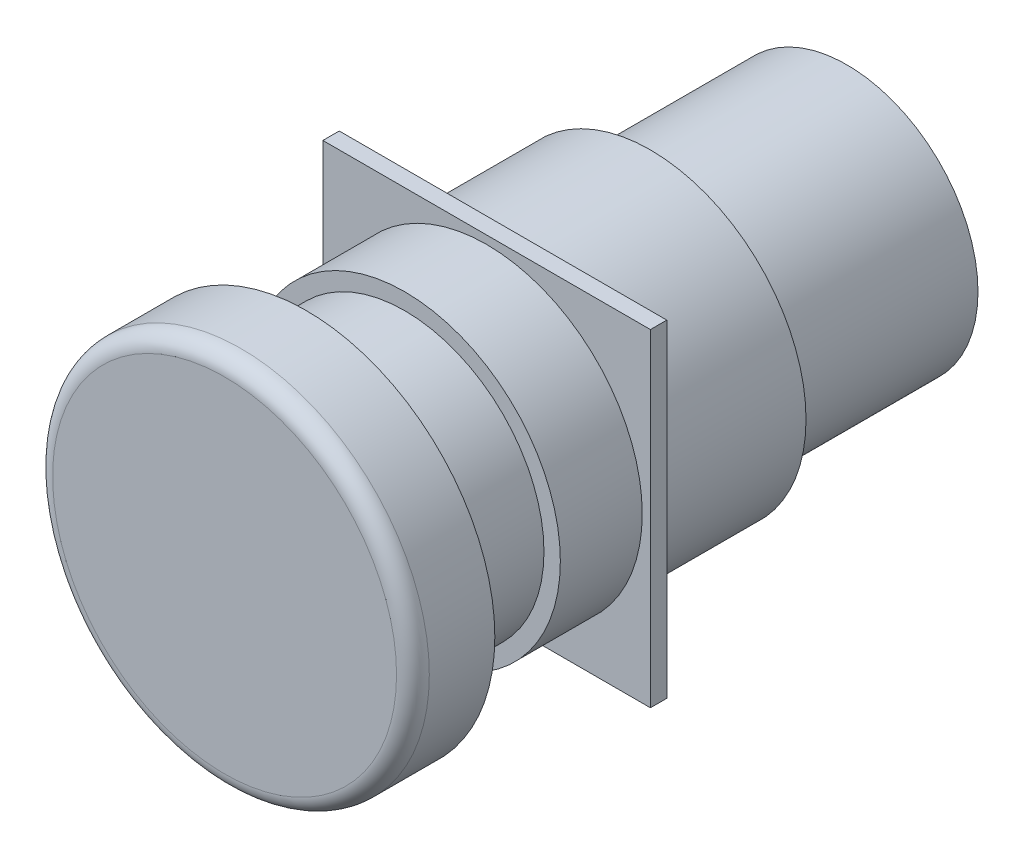
SolidWorks part; units mm, degrees
ref_plane "前视基准面" through (0, 0, 0) normal (0, 0, 1) x (1, 0, 0)
ref_plane "上视基准面" through (0, 0, 0) normal (0, 1, 0) x (1, 0, 0)
ref_plane "右视基准面" through (0, 0, 0) normal (1, 0, 0) x (0, 0, -1)
other "Configuration Table"
sketch "草图1" plane through (0, 0, 0) normal (0, 1, 0) x (1, 0, 0)
  line L0 (11.5, 0) -> (0, 0)
  line L1 (0, 0) -> (0, -5)
  line L2 (0, -5) -> (11.5, -5)
  line L3 (11.5, -5) -> (11.5, 0)
  line L4 (0, 0) -> (0, -5) construction
  dimension "D1" = 11.5
  dimension "D2" = 5
revolve "旋转1" add sketch "草图1" angle 360 about L4
sketch "草图2" plane through (0, 0, 0) normal (0, 0, -1) x (-1, 0, 0)
  circle A0 centre (0, 0) radius 10.5
  dimension "D1" = 21
extrude "切除-拉伸1" cut sketch "草图2" against normal blind 4
sketch "草图3" plane through (0, 0, 4) normal (0, 0, -1) x (-1, 0, 0)
  circle A0 centre (0, 0) radius 8.5
  dimension "D1" = 17
extrude "凸台-拉伸1" add sketch "草图3" along normal blind 10
ref_plane "基准面1" through (0, 0, -6) normal (0, 0, 1) x (1, 0, 0)
sketch "草图4" plane through (0, 0, -6) normal (0, 0, 1) x (1, 0, 0)
  circle A0 centre (0, 0) radius 9.5
  dimension "D1" = 19
extrude "凸台-拉伸2" add sketch "草图4" against normal blind 5
ref_plane "基准面2" through (0, 0, -11) normal (0, 0, 1) x (1, 0, 0)
sketch "草图5" plane through (0, 0, -11) normal (0, 0, 1) x (1, 0, 0)
  line L0 (10, -10) -> (10, 10)
  line L1 (10, 10) -> (-10, 10)
  line L2 (-10, 10) -> (-10, -10)
  line L3 (-10, -10) -> (10, -10)
  dimension "D1" = 20
  dimension "D2" = 20
extrude "凸台-拉伸3" add sketch "草图5" against normal blind 1
sketch "草图6" plane through (0, 0, -12) normal (0, 0, -1) x (-1, 0, 0)
  line L0 (10, 10) -> (10, -10) construction
  line L1 (10, -10) -> (-10, -10) construction
  circle A0 centre (0, 0) radius 9.5
  dimension "D1" = 19
  dimension "D2" = 10
  dimension "D3" = 10
extrude "凸台-拉伸4" add sketch "草图6" along normal blind 9
sketch "草图7" plane through (0, 0, -21) normal (0, 0, -1) x (-1, 0, 0)
  circle A0 centre (0, 0) radius 8
  dimension "D1" = 16
extrude "凸台-拉伸5" add sketch "草图7" along normal blind 12
fillet "圆角1" radius 1 1 edges at (11.5, 0, 5)
